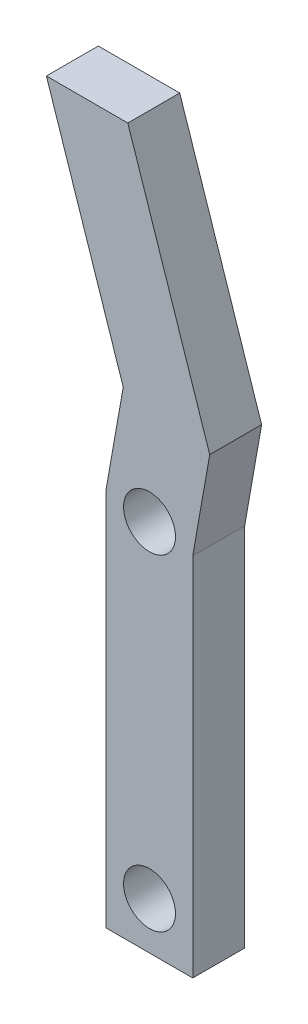
SolidWorks part; units mm, degrees
material "Plastique personnalisé"
ref_plane "Plan de face" through (0, 0, 0) normal (0, 0, 1) x (1, 0, 0)
ref_plane "Plan de dessus" through (0, 0, 0) normal (0, 1, 0) x (1, 0, 0)
ref_plane "Plan de droite" through (0, 0, 0) normal (1, 0, 0) x (0, 0, -1)
sketch "Esquisse1" plane through (0, 0, 0) normal (0, 0, 1) x (1, 0, 0)
  line L0 (0, 22) -> (0.9804, 27.5679)
  line L1 (0, 0) -> (5, 0)
  line L2 (0, 0) -> (0, 22)
  line L4 (5, 0) -> (5, 21.1275)
  line L7 (0.9804, 27.5679) -> (-3.4601, 40.9212)
  line L8 (0, 2.7244) -> (5, 2.7244) construction
  line L9 (5.9804, 26.6875) -> (5, 21.1275) construction
  line L12 (5.9804, 26.6875) -> (5, 21.1275)
  line L13 (5.9804, 26.6875) -> (1.2471, 40.9212)
  line L14 (1.2471, 40.9212) -> (-3.4601, 40.9212)
  circle A0 centre (2.5, 2.7244) radius 1.5
  circle A1 centre (2.5, 21.5844) radius 1.5
  dimension "D6" = 3
  dimension "D7" = 3
  dimension "D1" = 22
  dimension "D2" = 5.56
  dimension "D3" = 5.5679
  dimension "D4" = 5
  dimension "D5" = 5
  dimension "D8" = 2.7244
  dimension "D9" = 170
  dimension "D10" = 21.1275
  dimension "D11" = 15
  dimension "D12" = 18.86
  dimension "D13" = 2.5
  dimension "D14" = 151.62
extrude "Boss.-Extru.1" add sketch "Esquisse1" along normal blind 3
